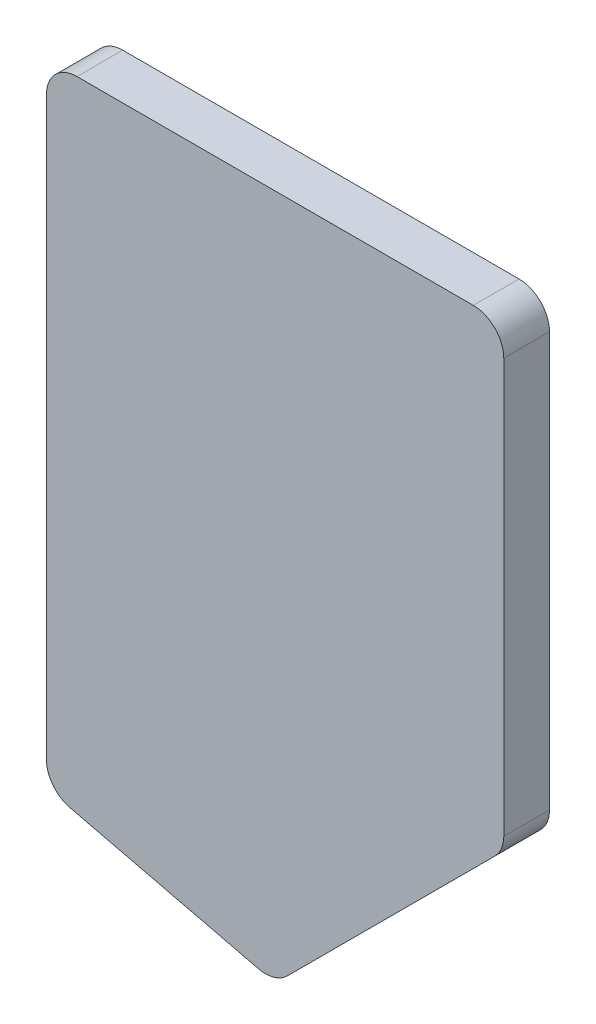
SolidWorks part; units mm, degrees
ref_plane "Front Plane" through (0, 0, 0) normal (0, 0, 1) x (1, 0, 0)
ref_plane "Top Plane" through (0, 0, 0) normal (0, 1, 0) x (1, 0, 0)
ref_plane "Right Plane" through (0, 0, 0) normal (1, 0, 0) x (0, 0, -1)
sketch "Sketch1" plane through (0, 0, 0) normal (0, 0, 1) x (1, 0, 0)
  line L0 (0, 103.5) -> (0, -103.5) construction
  line L1 (0, 103.5) -> (0, -103.5)
  line L2 (0, 103.5) -> (150, 103.5)
  line L3 (150, 103.5) -> (150, -46.5)
  line L4 (150, -46.5) -> (75, -121.5)
  line L5 (75, -121.5) -> (0, -103.5)
  point P4 (0, 0)
  point P7 (0, 0)
  dimension "D1" = 207
  dimension "D2" = 150
  dimension "D3" = 150
  dimension "D4" = 106.066
  dimension "D5" = 75
extrude "Boss-Extrude1" add sketch "Sketch1" along normal blind 15
fillet "Fillet1" radius 10 1 edges at (0, -103.5, 7.5)
fillet "Fillet2" radius 10 1 edges at (75, -121.5, 7.5)
fillet "Fillet4" radius 10 1 edges at (150, -46.5, 7.5)
fillet "Fillet5" radius 10 1 edges at (150, 103.5, 7.5)
fillet "Fillet6" radius 10 1 edges at (0, 103.5, 7.5)
sketch "Sketch2" plane through (0, 0, 0) normal (0, 0, -1) x (-1, 0, 0)
  line L32 (-12.2355, 3.5624) -> (-83.5816, 94.4213)
  line L33 (-87.7832, 0) -> (-83.5816, 0)
  line L34 (-87.7832, 0) -> (-87.7832, 94.4213)
  line L35 (-87.7832, 94.4213) -> (-83.5816, 94.4213)
  line L36 (-83.5816, 3.5624) -> (-83.5816, 89.1701)
  line L37 (-87.7832, 0) -> (-46.5977, 0)
  line L38 (-87.7832, 0) -> (-87.7832, 3.5624)
  line L39 (-83.5816, 3.5624) -> (-46.5977, 3.5624)
  line L40 (-12.2355, 0) -> (-12.2355, 3.5624)
  line L41 (-15.0858, 3.5624) -> (-42.6036, 37.9548)
  line L42 (-42.6036, 3.5624) -> (-15.0858, 3.5624)
  line L44 (-42.6036, 3.5624) -> (-42.6036, 37.9548)
  line L46 (-46.5977, 3.5624) -> (-46.5977, 42.9468)
  line L47 (-42.6036, 0) -> (-12.2355, 0)
  line L48 (-46.5977, 0) -> (-42.6036, 0)
  line L49 (-46.5977, 42.9468) -> (-83.5816, 89.1701)
extrude "Cut-Extrude1" cut sketch "Sketch2" against normal blind 2 contours L37 L48 L47 L40 L32 L35 L34 L33 L49 L46 L39 L36 L42 L44 L41
